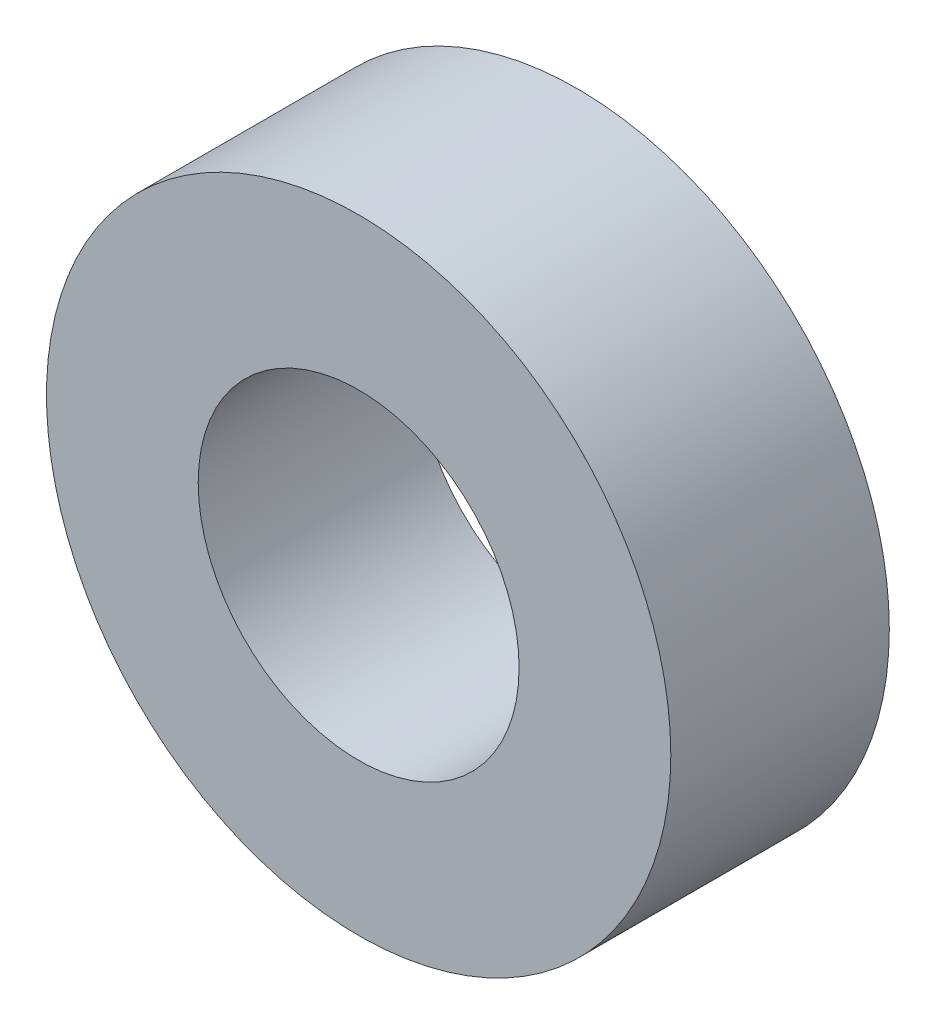
SolidWorks part; units mm, degrees
material "Nylon 101"
ref_plane "Front Plane" through (0, 0, 0) normal (0, 0, 1) x (1, 0, 0)
ref_plane "Top Plane" through (0, 0, 0) normal (0, 1, 0) x (1, 0, 0)
ref_plane "Right Plane" through (0, 0, 0) normal (1, 0, 0) x (0, 0, -1)
sketch "Sketch1" plane through (0, 0, 0) normal (0, 0, 1) x (1, 0, 0)
  circle A0 centre (0, 0) radius 6.35
  circle A1 centre (0, 0) radius 3.2639
  dimension "D1" = 12.7
  dimension "D2" = 6.5278
extrude "Boss-Extrude1" add sketch "Sketch1" along normal blind 4.445
